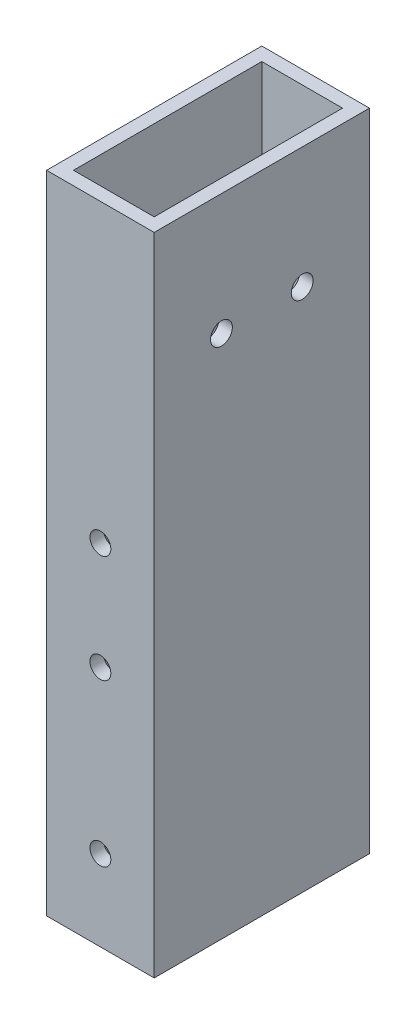
SolidWorks part; units mm, degrees
ref_plane "Front Plane" through (0, 0, 0) normal (0, 0, 1) x (1, 0, 0)
ref_plane "Top Plane" through (0, 0, 0) normal (0, 1, 0) x (1, 0, 0)
ref_plane "Right Plane" through (0, 0, 0) normal (1, 0, 0) x (0, 0, -1)
sketch "Sketch1" plane through (0, 0, 0) normal (0, 1, 0) x (1, 0, 0)
  line L0 (3.175, 47.625) -> (22.225, 47.625)
  line L1 (0, 0) -> (25.4, 0)
  line L2 (0, 0) -> (0, 50.8)
  line L3 (0, 50.8) -> (25.4, 50.8)
  line L4 (25.4, 0) -> (25.4, 50.8)
  line L5 (22.225, 3.175) -> (22.225, 47.625)
  line L6 (3.175, 3.175) -> (22.225, 3.175)
  line L7 (3.175, 3.175) -> (3.175, 47.625)
  dimension "D1" = 50.8
  dimension "D2" = 25.4
  dimension "D3" = 3.175
extrude "Boss-Extrude1" add sketch "Sketch1" along normal blind 152.4
sketch "Sketch2" plane through (0, 0, 0) normal (0, 0, 1) x (1, 0, 0)
  circle A0 centre (12.7, 82.55) radius 2.4638
  circle A1 centre (12.7, 57.15) radius 2.4638
  circle A2 centre (12.7, 19.05) radius 2.4638
extrude "Cut-Extrude1" cut sketch "Sketch2" against normal through all
hole_wizard "13/64 (0.20313) Diameter Hole1" positions "Sketch3" profile "Sketch4" hole size "13/64" standard "ANSI Inch" end condition through all
sketch "Sketch3" plane through (0, 0, 0) normal (-1, 0, 0) x (0, 0, 1)
  point P0 (-34.925, 123.822)
  point P3 (-15.875, 123.822)
sketch "Sketch4" plane through (0, 123.822, -34.925) normal (0, 1, 0) x (0, 0, 1)
  line L0 (0, 0) -> (0, 25.4)
  line L1 (0, 25.4) -> (2.5798, 25.4)
  line L2 (2.5798, 25.4) -> (2.5798, 0)
  line L5 (2.5798, 0) -> (0, 0)
  line L11 (0, -6.35) -> (0, 107.95) construction
  dimension "Thru Hole Dia." = 5.1595
  dimension "Thru Hole Depth" = 25.4
